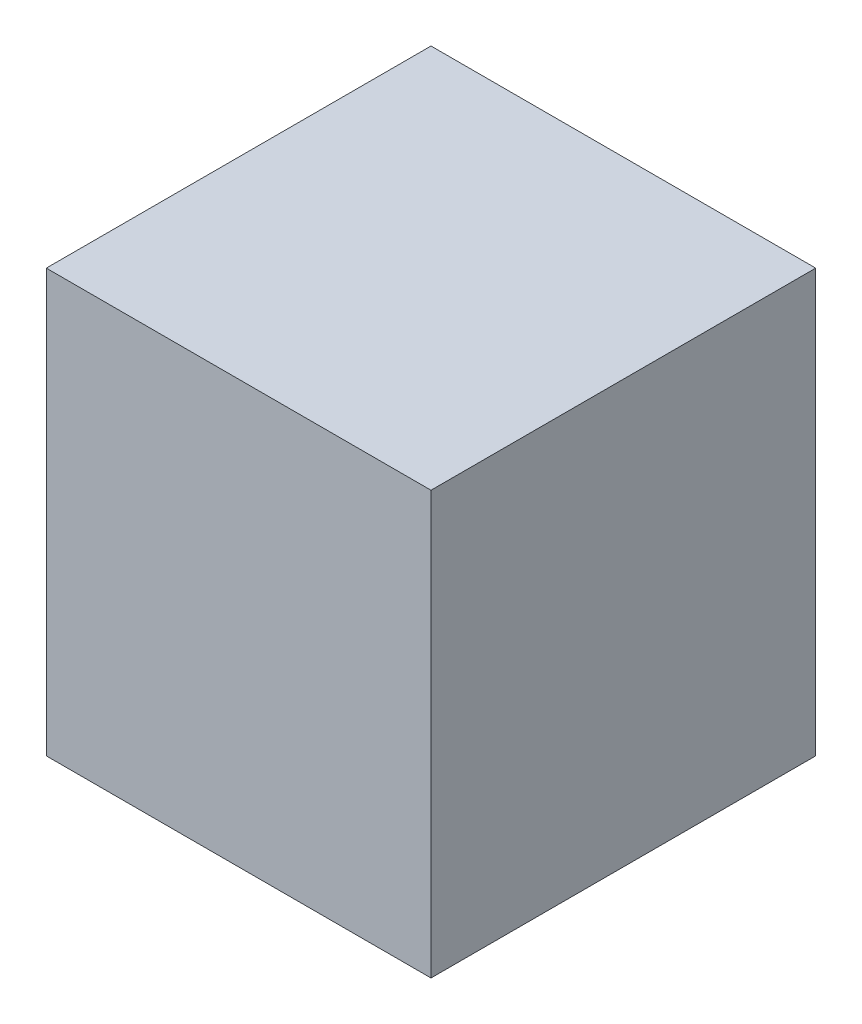
SolidWorks part; units mm, degrees
ref_plane "Front Plane" through (0, 0, 0) normal (0, 0, 1) x (1, 0, 0)
ref_plane "Top Plane" through (0, 0, 0) normal (0, 1, 0) x (1, 0, 0)
ref_plane "Right Plane" through (0, 0, 0) normal (1, 0, 0) x (0, 0, -1)
sketch "Sketch1" plane through (0, 0, 0) normal (0, 1, 0) x (1, 0, 0)
  line L1 (-25.5, 25.5) -> (25.5, 25.5)
  line L2 (-25.5, 25.5) -> (-25.5, -25.5)
  line L3 (-25.5, -25.5) -> (25.5, -25.5)
  line L4 (25.5, 25.5) -> (25.5, -25.5)
  line L5 (-25.5, 25.5) -> (25.5, -25.5) construction
  line L6 (-25.5, -25.5) -> (25.5, 25.5) construction
  point P0 (0, 0)
  dimension "D1" = 51
extrude "Boss-Extrude1" add sketch "Sketch1" along normal blind 56
